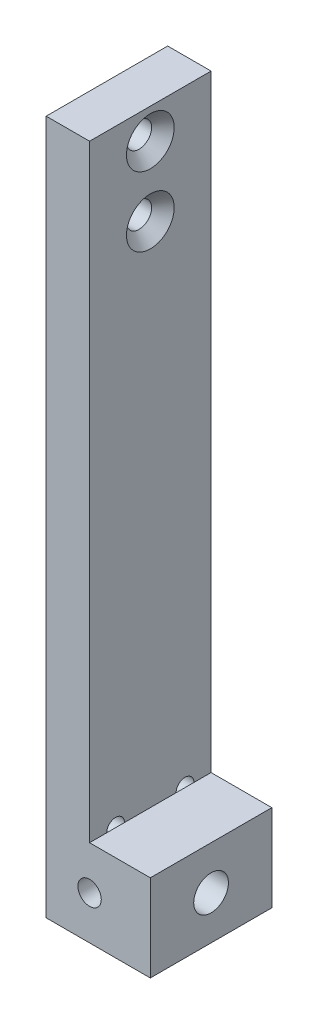
SolidWorks part; units mm, degrees
ref_plane "前基準面" through (0, 0, 0) normal (0, 0, 1) x (1, 0, 0)
ref_plane "上基準面" through (0, 0, 0) normal (0, 1, 0) x (1, 0, 0)
ref_plane "右基準面" through (0, 0, 0) normal (1, 0, 0) x (0, 0, -1)
sketch "草圖1" plane through (0, 0, 0) normal (1, 0, 0) x (0, 0, -1)
  line L1 (-7, -40) -> (7, -40)
  line L2 (-7, -40) -> (-7, 40)
  line L3 (-7, 40) -> (7, 40)
  line L4 (7, -40) -> (7, 40)
  line L5 (-7, -40) -> (7, 40) construction
  line L6 (-7, 40) -> (7, -40) construction
  point P0 (0, 0)
  dimension "D1" = 80
  dimension "D2" = 14
extrude "填料-伸長1" add sketch "草圖1" along normal blind 5
sketch "草圖14" plane through (5, 0, 0) normal (1, 0, 0) x (0, 0, -1)
  line L0 (7, -40) -> (7, 40) construction
  line L1 (-7, -40) -> (7, -40)
  line L2 (-7, -40) -> (-7, -30)
  line L3 (-7, -30) -> (7, -30)
  line L4 (7, -40) -> (7, -30)
  dimension "D1" = 10
extrude "填料-伸長2" add sketch "草圖14" along normal blind 7
hole_wizard "M2.5 錐坑平頭螺釘的錐孔1" positions "草圖3" profile "草圖5" countersink size "M2.5" standard "ISO" end condition through all
sketch "草圖3" plane through (5, 0, 0) normal (1, 0, 0) x (0, 0, -1)
  line L0 (7, 40) -> (-7, 40) construction
  point P0 (0, 36.5)
  point P2 (0, 28.5)
  dimension "D1" = 8
  dimension "D2" = 3.5
sketch "草圖5" plane through (5, 36.5, 0) normal (0, 1, 0) x (0, 0, -1)
  line L0 (0, 0) -> (0, 5)
  line L1 (0, 5) -> (1.45, 5)
  line L2 (1.45, 5) -> (1.45, 1.3)
  line L3 (1.45, 1.3) -> (2.75, 0)
  line L5 (2.75, 0) -> (0, 0)
  line L6 (-1.45, 1.3) -> (-2.75, 0) construction
  line L11 (0, -6.35) -> (0, 107.95) construction
  dimension "貫穿孔直徑" = 2.9
  dimension "貫穿孔深度" = 5
  dimension "近端錐孔直徑" = 5.5
  dimension "近端錐孔角度" = 90
hole_wizard "M2.5 螺紋孔1" positions "草圖8" profile "草圖9" tap size "M2.5" standard "ISO"
sketch "草圖8" plane through (5, 0, 0) normal (1, 0, 0) x (0, 0, -1)
  line L0 (7, -30) -> (7, 40) construction
  line L1 (-4, -30) -> (4, -30) construction
  line L3 (-7, -40) -> (7, -40) construction
  point P0 (4, -30)
  point P5 (-4, -30)
  dimension "D1" = 3
  dimension "D2" = 8
  dimension "D3" = 10
cosmetic thread "鑽孔螺紋2" parameters "D2"=2.5
cosmetic thread "鑽孔螺紋8" parameters "D2"=2.5
sketch "草圖9" plane through (5, -30, -4) normal (0, 1, 0) x (0, 0, -1)
  line L0 (0, 0) -> (0, 5)
  line L1 (0, 5) -> (1.025, 5)
  line L2 (1.025, 5) -> (1.025, 0)
  line L5 (1.025, 0) -> (0, 0)
  line L11 (0, -6.35) -> (0, 107.95) construction
  dimension "貫穿螺孔鑽直徑" = 2.05
  dimension "貫穿螺孔鑽深度" = 5
hole_wizard "M3 螺紋孔1" [suppressed] positions "草圖10" profile "草圖11" tap size "M3" standard "ISO"
sketch "草圖10" plane through (0, 0, -7) normal (0, 0, -1) x (-1, 0, 0)
  line L0 (-8, -30) -> (-8, 30) construction
  line L1 (-8, -30) -> (0, -30) construction
  point P0 (-5, -25)
  dimension "D1" = 3
  dimension "D2" = 5
sketch "草圖11" plane through (5, -25, -7) normal (1, 0, 0) x (0, 1, 0)
  line L0 (0, 0) -> (0, 14)
  line L1 (0, 14) -> (1.25, 14)
  line L2 (1.25, 14) -> (1.25, 0.275)
  line L3 (1.25, 0.275) -> (1.525, 0)
  line L5 (1.525, 0) -> (0, 0)
  line L6 (-1.25, 0.275) -> (-1.525, 0) construction
  line L11 (0, -6.35) -> (0, 107.95) construction
  dimension "貫穿螺孔鑽直徑" = 2.5
  dimension "貫穿螺孔鑽深度" = 14
  dimension "近端錐孔直徑" = 3.05
  dimension "近端錐孔角度" = 90
cosmetic thread "鑽孔螺紋3" [suppressed] parameters "D2"=3
mirror "鏡射1" [suppressed] about plane through (0, 0, 0) normal (0, 0, 1)
sketch "草圖15" plane through (0, 0, 0) normal (-1, 0, 0) x (0, 0, 1)
  line L0 (7, -40) -> (-7, -40) construction
  circle A0 centre (0, -35) radius 2
  dimension "D1" = 4
  dimension "D2" = 5
extrude "除料-伸長2" cut sketch "草圖15" against normal through all
hole_wizard "Ø1.0mm 定位孔2" positions "草圖16" profile "草圖17" hole size "Ø1.0" standard "ISO"
sketch "草圖16" plane through (0, 0, -7) normal (0, 0, -1) x (-1, 0, 0)
  line L0 (0, -40) -> (0, 40) construction
  line L1 (-12, -40) -> (0, -40) construction
  point P0 (-5, -35)
  dimension "D1" = 5
  dimension "D2" = 5
sketch "草圖17" plane through (5, -35, -7) normal (1, 0, 0) x (0, 1, 0)
  line L0 (0, 0) -> (0, 14)
  line L1 (0, 14) -> (1.35, 14)
  line L2 (1.35, 14) -> (1.35, 0)
  line L5 (1.35, 0) -> (0, 0)
  line L11 (0, -6.35) -> (0, 107.95) construction
  dimension "貫穿孔直徑" = 2.7
  dimension "貫穿孔深度" = 14
mirror "鏡射2" about plane through (0, 0, 0) normal (0, 0, 1) of "Ø1.0mm 定位孔2"
hole_wizard "Ø1.0mm 定位孔1" positions "草圖18" profile "草圖19" hole size "Ø1.0" standard "ISO"
sketch "草圖18" plane through (0, -40, 0) normal (0, -1, 0) x (-1, 0, 0)
  line L0 (-12, 7) -> (0, 7) construction
  line L1 (-12, -7) -> (-12, 7) construction
  point P0 (-8, 0)
  dimension "D1" = 7
  dimension "D2" = 4
sketch "草圖19" plane through (8, -40, 0) normal (1, 0, 0) x (0, 0, -1)
  line L0 (0, 0) -> (0, 3)
  line L1 (0, 3) -> (1.35, 3)
  line L2 (1.35, 3) -> (1.35, 0)
  line L5 (1.35, 0) -> (0, 0)
  line L11 (0, -6.35) -> (0, 107.95) construction
  dimension "貫穿孔直徑" = 2.7
  dimension "貫穿孔深度" = 3
